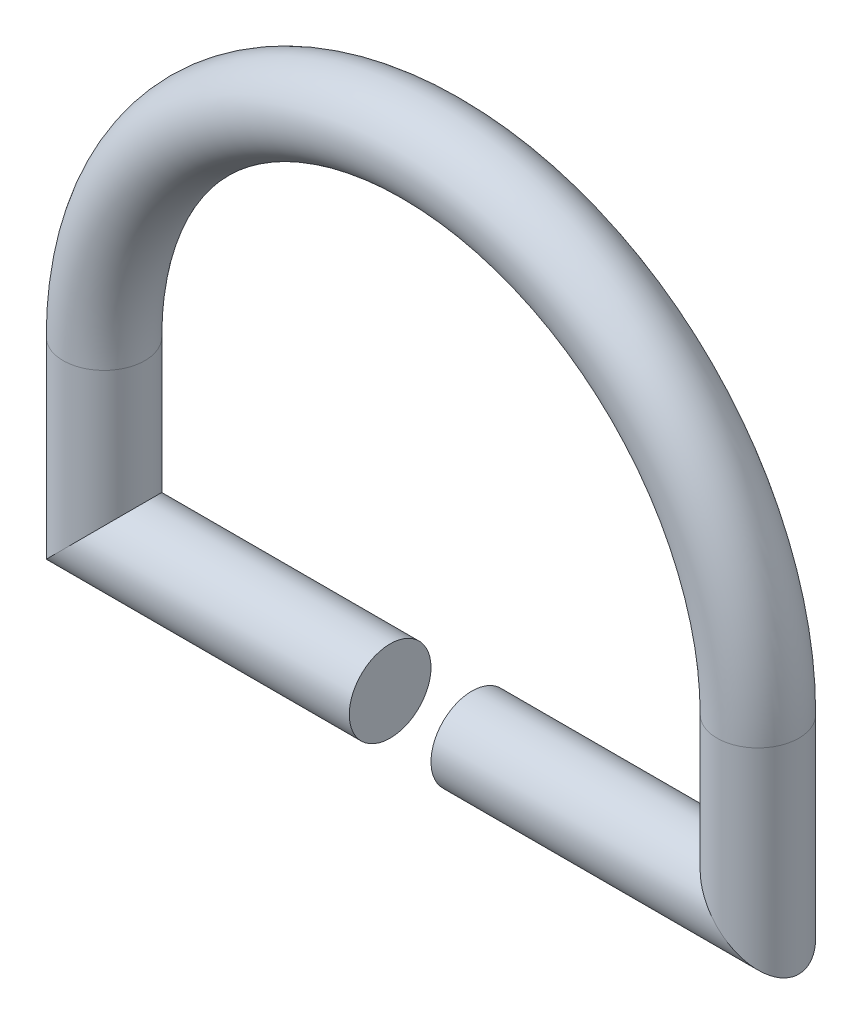
SolidWorks part; units mm, degrees
ref_plane "前视基准面" through (0, 0, 0) normal (0, 0, 1) x (1, 0, 0)
ref_plane "上视基准面" through (0, 0, 0) normal (0, 1, 0) x (1, 0, 0)
ref_plane "右视基准面" through (0, 0, 0) normal (1, 0, 0) x (0, 0, -1)
other "Configuration Table"
sketch "草图1" plane through (0, 0, 0) normal (0, 0, 1) x (1, 0, 0)
  line L0 (-0.5, 0) -> (-4, 0)
  line L1 (-4, 0) -> (-4, 2)
  line L2 (0.5, 0) -> (4, 0)
  line L3 (4, 0) -> (4, 2)
  arc A0 (-4, 2) -> (4, 2) centre (0, 2) cw
  dimension "D4" = 2
  dimension "D1" = 0.5
  dimension "D2" = 0.5
  dimension "D3" = 8
ref_plane "基准面1" through (-0.5, 0, 0) normal (1, 0, 0) x (0, 0, -1)
sketch "草图2" plane through (-0.5, 0, 0) normal (1, 0, 0) x (0, 0, -1)
  circle A0 centre (0, 0) radius 0.5
  dimension "D1" = 1
sweep "扫描1" add profiles "草图2" path "草图1"
